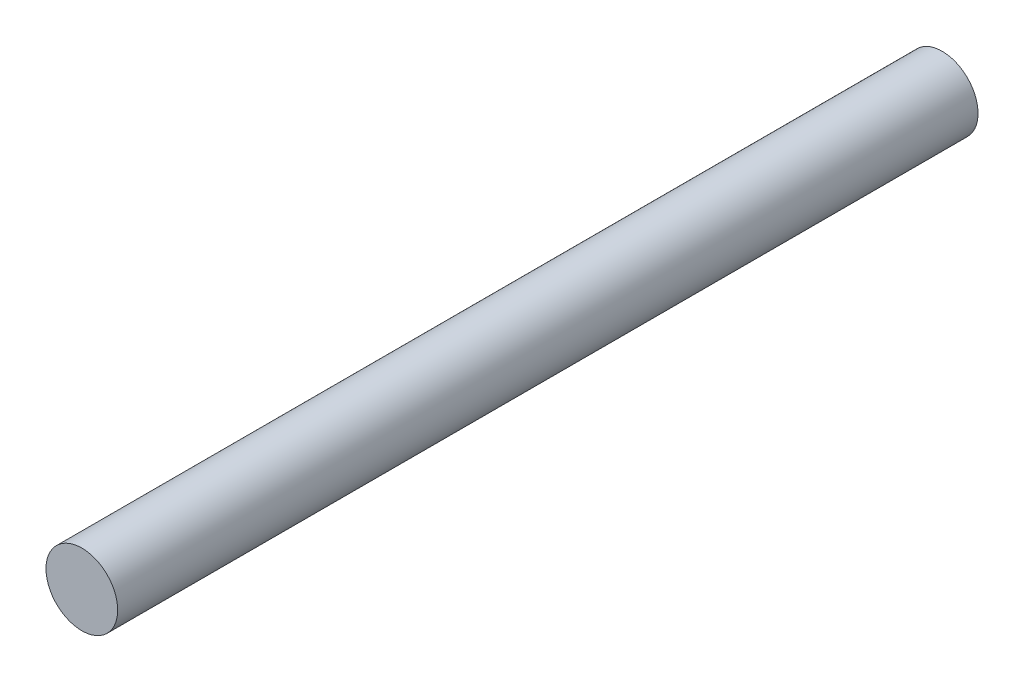
SolidWorks part; units mm, degrees
ref_plane "前视基准面" through (0, 0, 0) normal (0, 0, 1) x (1, 0, 0)
ref_plane "上视基准面" through (0, 0, 0) normal (0, 1, 0) x (1, 0, 0)
ref_plane "右视基准面" through (0, 0, 0) normal (1, 0, 0) x (0, 0, -1)
sketch "草图1" plane through (0, 0, 0) normal (0, 0, 1) x (1, 0, 0)
  circle A0 centre (0, 0) radius 1.75
  dimension "D1" = 3.5
extrude "凸台-拉伸1" add sketch "草图1" along normal blind 42
cosmetic thread "装饰螺纹线1" parameters "D2"=2.013
cosmetic thread "装饰螺纹线2" parameters "D2"=2.459
